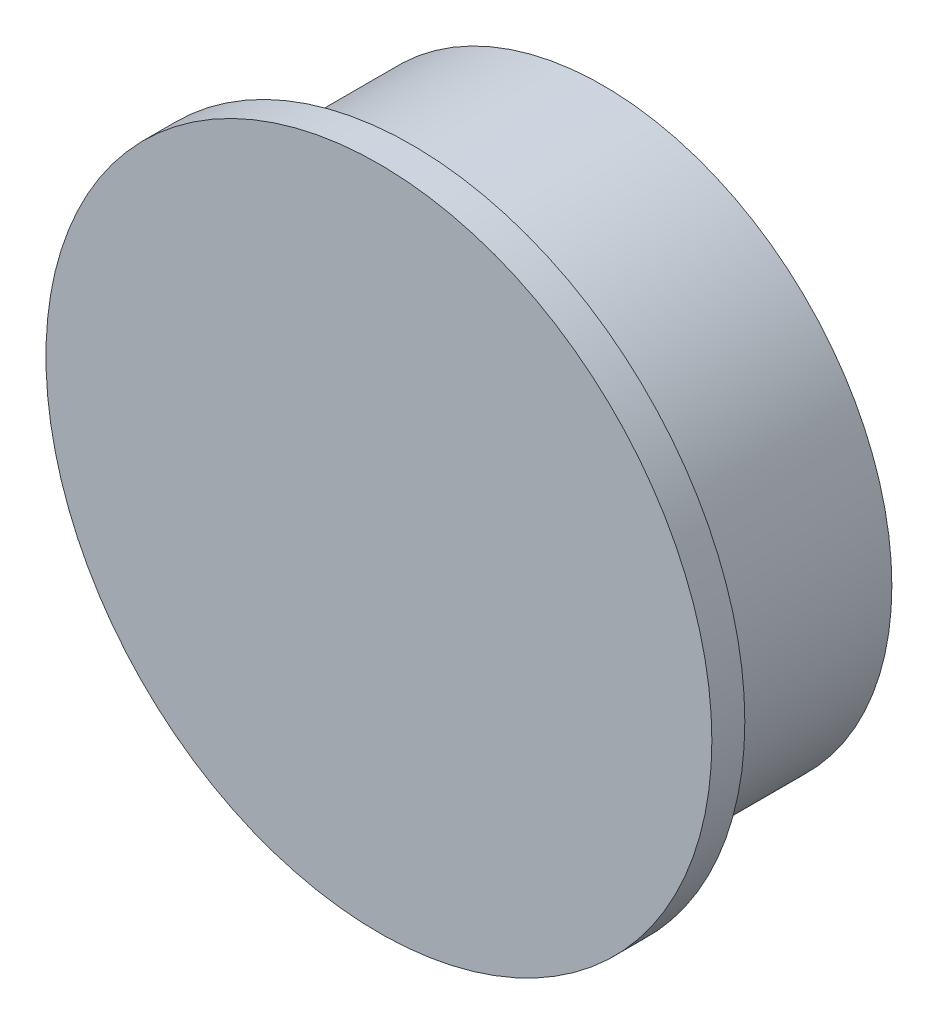
SolidWorks part; units mm, degrees
material "Silicon Rubber"
ref_plane "Front Plane" through (0, 0, 0) normal (0, 0, 1) x (1, 0, 0)
ref_plane "Top Plane" through (0, 0, 0) normal (0, 1, 0) x (1, 0, 0)
ref_plane "Right Plane" through (0, 0, 0) normal (1, 0, 0) x (0, 0, -1)
sketch "Sketch1" plane through (0, 0, 0) normal (0, 0, 1) x (1, 0, 0)
  circle A0 centre (34.6978, 180.4141) radius 30.5
  dimension "D1" = 61
extrude "Boss-Extrude1" add sketch "Sketch1" along normal blind 20.18
sketch "Sketch2" plane through (0, 0, 20.18) normal (0, 0, 1) x (1, 0, 0)
  circle A0 centre (34.6978, 180.4141) radius 35.155
  point P5 (34.6978, 180.4141)
  point P6 (34.6978, 180.4141)
  dimension "D1" = 70.31
extrude "Boss-Extrude2" add sketch "Sketch2" along normal blind 3.48
